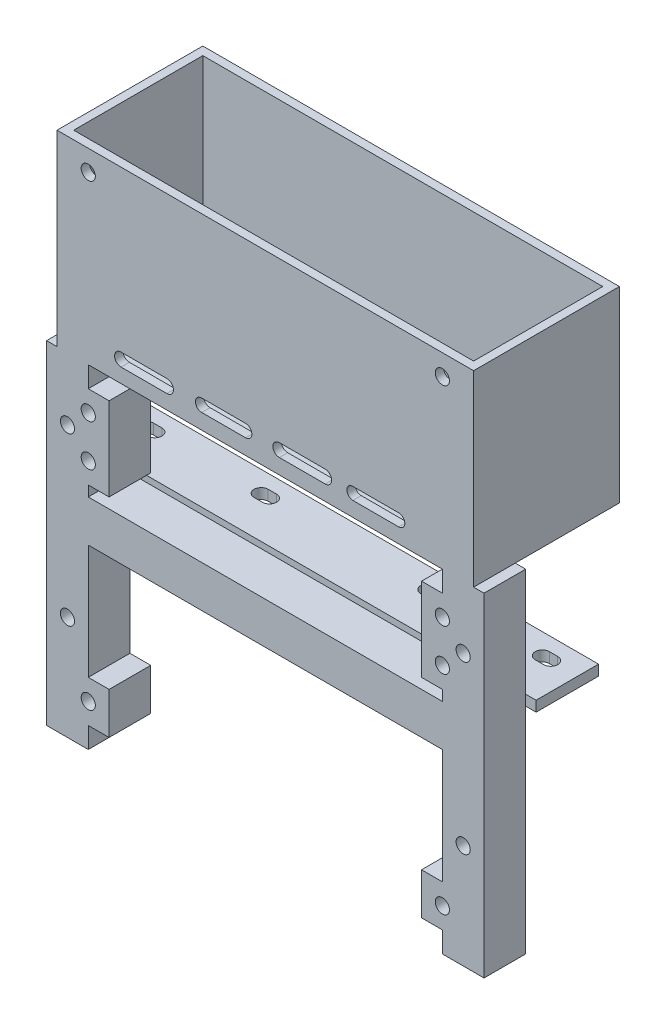
SolidWorks part; units mm, degrees
ref_plane "前视基准面" through (0, 0, 0) normal (0, 0, 1) x (1, 0, 0)
ref_plane "上视基准面" through (0, 0, 0) normal (0, 1, 0) x (1, 0, 0)
ref_plane "右视基准面" through (0, 0, 0) normal (1, 0, 0) x (0, 0, -1)
other "Configuration Table"
sketch "V3 box footprint 100 x 45 mm" plane through (0, 0, 0) normal (0, 0, 1) x (1, 0, 0)
  line L1 (-50, 0) -> (50, 0)
  line L2 (-50, 0) -> (-50, 45)
  line L3 (-50, 45) -> (50, 45)
  line L4 (50, 0) -> (50, 45)
extrude "V3 box height 35 mm" add sketch "V3 box footprint 100 x 45 mm" along normal blind 35
sketch "V3 rear opening 96 x 31 mm" plane through (0, 45, 0) normal (0, 1, 0) x (1, 0, 0)
  line L1 (-48, -2) -> (48, -2)
  line L2 (-48, -2) -> (-48, -33)
  line L3 (-48, -33) -> (48, -33)
  line L4 (48, -2) -> (48, -33)
extrude "V3 cavity all walls 2 mm" cut sketch "V3 rear opening 96 x 31 mm" against normal blind 43
sketch "V3 square beams 10 x 10 pitch 95 mm" plane through (0, 0, 0) normal (0, -1, 0) x (1, 0, 0)
  line L1 (-52.5, 25) -> (-42.5, 25)
  line L2 (-52.5, 25) -> (-52.5, 35)
  line L3 (-52.5, 35) -> (-42.5, 35)
  line L4 (-42.5, 25) -> (-42.5, 35)
  line L6 (42.5, 25) -> (52.5, 25)
  line L7 (42.5, 25) -> (42.5, 35)
  line L8 (42.5, 35) -> (52.5, 35)
  line L9 (52.5, 25) -> (52.5, 35)
extrude "V3 forward beam length 65 mm" add sketch "V3 square beams 10 x 10 pitch 95 mm" along normal blind 65
sketch "V3 left PCB ear profile" plane through (-42.5, 0, 0) normal (1, 0, 0) x (0, 0, -1)
  line L1 (-25, -25) -> (-35, -25)
  line L2 (-25, -25) -> (-25, -15)
  line L3 (-25, -15) -> (-35, -15)
  line L4 (-35, -25) -> (-35, -15)
extrude "V3 left inward ear 5 mm" add sketch "V3 left PCB ear profile" along normal blind 5
sketch "V3 right PCB ear profile" plane through (42.5, 0, 0) normal (-1, 0, 0) x (0, 0, 1)
  line L1 (25, -25) -> (35, -25)
  line L2 (25, -25) -> (25, -15)
  line L3 (25, -15) -> (35, -15)
  line L4 (35, -25) -> (35, -15)
extrude "V3 right inward ear 5 mm" add sketch "V3 right PCB ear profile" along normal blind 5
sketch "V3 PCB roof pair pitch 85 mm" plane through (0, 0, 35) normal (0, 0, 1) x (1, 0, 0)
  circle A0 centre (-42.5, 40) radius 1.7
  circle A1 centre (42.5, 40) radius 1.7
extrude "V3 M3 roof holes diameter 3.4 mm" cut sketch "V3 PCB roof pair pitch 85 mm" against normal blind 2
sketch "V3 PCB forward pair row spacing 60 mm" plane through (0, 0, 35) normal (0, 0, 1) x (1, 0, 0)
  circle A0 centre (-42.5, -20) radius 1.7
  circle A1 centre (42.5, -20) radius 1.7
extrude "V3 M3 PCB ear holes" cut sketch "V3 PCB forward pair row spacing 60 mm" against normal blind 10
sketch "V3 chassis top holes width 95 depth 40 mm" plane through (0, 0, 35) normal (0, 0, 1) x (1, 0, 0)
  circle A0 centre (-47.5, -55) radius 1.7
  circle A1 centre (-47.5, -15) radius 1.7
  circle A2 centre (47.5, -55) radius 1.7
  circle A3 centre (47.5, -15) radius 1.7
extrude "V3 M3 beam top bottom holes" cut sketch "V3 chassis top holes width 95 depth 40 mm" against normal blind 10
sketch "V3 hanging plate offset 26 thickness 2.5 mm" plane through (0, 0, 25) normal (0, 0, -1) x (-1, 0, 0)
  line L1 (55, -28.5) -> (-55, -28.5)
  line L2 (55, -28.5) -> (55, -26)
  line L3 (55, -26) -> (-55, -26)
  line L4 (-55, -28.5) -> (-55, -26)
extrude "V3 mounting plate downward 15 mm width 110" add sketch "V3 hanging plate offset 26 thickness 2.5 mm" along normal blind 15
sketch "V3 slots 6 mm below beam underside centers 20 and 47.5" plane through (0, -28.5, 0) normal (0, -1, 0) x (1, 0, 0)
  line L0 (-48.5, 19) -> (-46.5, 19) construction
  line L1 (-48.5, 20.7) -> (-46.5, 20.7)
  line L2 (-48.5, 17.3) -> (-46.5, 17.3)
  line L3 (-21, 19) -> (-19, 19) construction
  line L4 (-21, 20.7) -> (-19, 20.7)
  line L5 (-21, 17.3) -> (-19, 17.3)
  line L6 (19, 19) -> (21, 19) construction
  line L7 (19, 20.7) -> (21, 20.7)
  line L8 (19, 17.3) -> (21, 17.3)
  line L9 (46.5, 19) -> (48.5, 19) construction
  line L10 (46.5, 20.7) -> (48.5, 20.7)
  line L11 (46.5, 17.3) -> (48.5, 17.3)
  arc A0 (-48.5, 20.7) -> (-48.5, 17.3) centre (-48.5, 19) ccw
  arc A1 (-46.5, 17.3) -> (-46.5, 20.7) centre (-46.5, 19) ccw
  arc A2 (-21, 20.7) -> (-21, 17.3) centre (-21, 19) ccw
  arc A3 (-19, 17.3) -> (-19, 20.7) centre (-19, 19) ccw
  arc A4 (19, 20.7) -> (19, 17.3) centre (19, 19) ccw
  arc A5 (21, 17.3) -> (21, 20.7) centre (21, 19) ccw
  arc A6 (46.5, 20.7) -> (46.5, 17.3) centre (46.5, 19) ccw
  arc A7 (48.5, 17.3) -> (48.5, 20.7) centre (48.5, 19) ccw
  point P2 (-47.5, 19)
  point P7 (-20, 19)
  point P14 (20, 19)
  point P21 (47.5, 19)
  dimension "D1" = 3.4
  dimension "D2" = 2
  dimension "D3" = 3.4
  dimension "D4" = 2
  dimension "D5" = 3.4
  dimension "D6" = 2
  dimension "D7" = 3.4
  dimension "D8" = 2
extrude "Four horizontal slots 3.4 x 5.4 mm" cut sketch "V3 slots 6 mm below beam underside centers 20 and 47.5" against normal blind 2.5
sketch "草图1" plane through (0, 0, 35) normal (0, 0, 1) x (1, 0, 0)
  line L0 (-34.6201, 5) -> (-23.6201, 5) construction
  line L1 (-34.6201, 6.488) -> (-23.6201, 6.488)
  line L2 (-34.6201, 3.512) -> (-23.6201, 3.512)
  line L3 (21.03, 5) -> (32.03, 5) construction
  line L6 (21.03, 6.488) -> (32.03, 6.488)
  line L7 (21.03, 3.512) -> (32.03, 3.512)
  arc A0 (-34.6201, 6.488) -> (-34.6201, 3.512) centre (-34.6201, 5) ccw
  arc A1 (-23.6201, 3.512) -> (-23.6201, 6.488) centre (-23.6201, 5) ccw
  arc A4 (21.03, 6.488) -> (21.03, 3.512) centre (21.03, 5) ccw
  arc A5 (32.03, 3.512) -> (32.03, 6.488) centre (32.03, 5) ccw
  point P2 (-29.1201, 5)
  point P9 (26.53, 5)
sketch "草图2" plane through (0, 0, 0) normal (0, 0, -1) x (-1, 0, 0)
  line L0 (-32.03, 5) -> (-21.03, 5) construction
  line L1 (-32.03, 6.4595) -> (-21.03, 6.4595)
  line L2 (-32.03, 3.5405) -> (-21.03, 3.5405)
  line L3 (23.6201, 5) -> (34.6201, 5) construction
  line L4 (23.6201, 6.5587) -> (34.6201, 6.5587)
  line L5 (23.6201, 3.4413) -> (34.6201, 3.4413)
  arc A0 (-32.03, 6.4595) -> (-32.03, 3.5405) centre (-32.03, 5) ccw
  arc A1 (-21.03, 3.5405) -> (-21.03, 6.4595) centre (-21.03, 5) ccw
  arc A2 (23.6201, 6.5587) -> (23.6201, 3.4413) centre (23.6201, 5) ccw
  arc A3 (34.6201, 3.4413) -> (34.6201, 6.5587) centre (34.6201, 5) ccw
  point P4 (-26.53, 5)
  point P9 (29.1201, 5)
extrude "切除-拉伸1" cut sketch "草图2" against normal through all
sketch "H crossmember 10 x 10 mm at beam midpoint" plane through (-42.5, 0, 0) normal (1, 0, 0) x (0, 0, -1)
  line L1 (-25, -37.5) -> (-35, -37.5)
  line L2 (-25, -37.5) -> (-25, -27.5)
  line L3 (-25, -27.5) -> (-35, -27.5)
  line L4 (-35, -37.5) -> (-35, -27.5)
extrude "H crossmember 85 mm" add sketch "H crossmember 10 x 10 mm at beam midpoint" along normal blind 85
sketch "Beam cavities 6 mm wide preserving screw collars" plane through (0, 0, 35) normal (0, 0, 1) x (1, 0, 0)
  line L1 (-50.5, -65) -> (-44.5, -65)
  line L2 (-50.5, -65) -> (-50.5, -59)
  line L3 (-50.5, -59) -> (-44.5, -59)
  line L4 (-44.5, -65) -> (-44.5, -59)
  line L6 (-50.5, -51) -> (-44.5, -51)
  line L7 (-50.5, -51) -> (-50.5, -24)
  line L8 (-50.5, -24) -> (-44.5, -24)
  line L9 (-44.5, -51) -> (-44.5, -24)
  line L11 (-50.5, -11) -> (-44.5, -11)
  line L12 (-50.5, -11) -> (-50.5, -2)
  line L13 (-50.5, -2) -> (-44.5, -2)
  line L14 (-44.5, -11) -> (-44.5, -2)
  line L16 (44.5, -65) -> (50.5, -65)
  line L17 (44.5, -65) -> (44.5, -59)
  line L18 (44.5, -59) -> (50.5, -59)
  line L19 (50.5, -65) -> (50.5, -59)
  line L21 (44.5, -51) -> (50.5, -51)
  line L22 (44.5, -51) -> (44.5, -24)
  line L23 (44.5, -24) -> (50.5, -24)
  line L24 (50.5, -51) -> (50.5, -24)
  line L26 (44.5, -11) -> (50.5, -11)
  line L27 (44.5, -11) -> (44.5, -2)
  line L28 (44.5, -2) -> (50.5, -2)
  line L29 (50.5, -11) -> (50.5, -2)
extrude "Longitudinal beam walls 2 mm - inner height 6 mm" cut sketch "Beam cavities 6 mm wide preserving screw collars" against normal blind 6 from offset 2
sketch "H crossmember cavity connects both beam cavities" plane through (0, 0, 35) normal (0, 0, 1) x (1, 0, 0)
  line L1 (-44.5, -35.5) -> (44.5, -35.5)
  line L2 (-44.5, -35.5) -> (-44.5, -29.5)
  line L3 (-44.5, -29.5) -> (44.5, -29.5)
  line L4 (44.5, -35.5) -> (44.5, -29.5)
extrude "H crossmember walls 2 mm" cut sketch "H crossmember cavity connects both beam cavities" against normal blind 6 from offset 2
sketch "草图7" plane through (0, 0, 35) normal (0, 0, 1) x (1, 0, 0)
  line L0 (-15.2765, 5.1864) -> (-4.7235, 5.1864) construction
  line L1 (-15.2765, 6.6864) -> (-4.7235, 6.6864)
  line L2 (-15.2765, 3.6864) -> (-4.7235, 3.6864)
  line L3 (3.3727, 5.1864) -> (14.3727, 5.1864) construction
  line L4 (3.3727, 6.6864) -> (14.3727, 6.6864)
  line L5 (3.3727, 3.6864) -> (14.3727, 3.6864)
  arc A0 (-15.2765, 6.6864) -> (-15.2765, 3.6864) centre (-15.2765, 5.1864) ccw
  arc A1 (-4.7235, 3.6864) -> (-4.7235, 6.6864) centre (-4.7235, 5.1864) ccw
  arc A2 (3.3727, 6.6864) -> (3.3727, 3.6864) centre (3.3727, 5.1864) ccw
  arc A3 (14.3727, 3.6864) -> (14.3727, 6.6864) centre (14.3727, 5.1864) ccw
  point P2 (-10, 5.1864)
  point P7 (8.8727, 5.1864)
sketch "草图8" plane through (0, 0, 0) normal (0, 0, -1) x (-1, 0, 0)
  line L0 (-14.3727, 5.1864) -> (-3.3727, 5.1864) construction
  line L1 (-14.3727, 6.733) -> (-3.3727, 6.733)
  line L2 (-14.3727, 3.6397) -> (-3.3727, 3.6397)
  line L3 (4.7235, 5.1864) -> (15.2765, 5.1864) construction
  line L4 (4.7235, 6.6864) -> (15.2765, 6.6864)
  line L5 (4.7235, 3.6864) -> (15.2765, 3.6864)
  arc A0 (-14.3727, 6.733) -> (-14.3727, 3.6397) centre (-14.3727, 5.1864) ccw
  arc A1 (-3.3727, 3.6397) -> (-3.3727, 6.733) centre (-3.3727, 5.1864) ccw
  arc A2 (4.7235, 6.6864) -> (4.7235, 3.6864) centre (4.7235, 5.1864) ccw
  arc A3 (15.2765, 3.6864) -> (15.2765, 6.6864) centre (15.2765, 5.1864) ccw
  point P4 (-8.8727, 5.1864)
  point P9 (10, 5.1864)
extrude "切除-拉伸4" cut sketch "草图8" against normal through all
sketch "V6 extend 10 x 10 hollow beams with 2 mm walls" plane through (0, -65, 0) normal (0, -1, 0) x (1, 0, 0)
  line L1 (-52.5, 25) -> (-42.5, 25)
  line L2 (-52.5, 25) -> (-52.5, 35)
  line L3 (-52.5, 35) -> (-42.5, 35)
  line L4 (-42.5, 25) -> (-42.5, 35)
  line L6 (-50.5, 27) -> (-44.5, 27)
  line L7 (-50.5, 27) -> (-50.5, 33)
  line L8 (-50.5, 33) -> (-44.5, 33)
  line L9 (-44.5, 27) -> (-44.5, 33)
  line L11 (42.5, 25) -> (52.5, 25)
  line L12 (42.5, 25) -> (42.5, 35)
  line L13 (42.5, 35) -> (52.5, 35)
  line L14 (52.5, 25) -> (52.5, 35)
  line L16 (44.5, 27) -> (50.5, 27)
  line L17 (44.5, 27) -> (44.5, 33)
  line L18 (44.5, 33) -> (50.5, 33)
  line L19 (50.5, 27) -> (50.5, 33)
extrude "V6 hollow beam extensions 15 mm" add sketch "V6 extend 10 x 10 hollow beams with 2 mm walls" along normal blind 15
sketch "V6 four full-depth PCB pads centers x42.5 y-70 and -10" plane through (0, 0, 35) normal (0, 0, 1) x (1, 0, 0)
  line L1 (-52.5, -75) -> (-37.5, -75)
  line L2 (-52.5, -75) -> (-52.5, -65)
  line L3 (-52.5, -65) -> (-37.5, -65)
  line L4 (-37.5, -75) -> (-37.5, -65)
  line L6 (37.5, -75) -> (52.5, -75)
  line L7 (37.5, -75) -> (37.5, -65)
  line L8 (37.5, -65) -> (52.5, -65)
  line L9 (52.5, -75) -> (52.5, -65)
  line L11 (-52.5, -15) -> (-37.5, -15)
  line L12 (-52.5, -15) -> (-52.5, -5)
  line L13 (-52.5, -5) -> (-37.5, -5)
  line L14 (-37.5, -15) -> (-37.5, -5)
  line L16 (37.5, -15) -> (52.5, -15)
  line L17 (37.5, -15) -> (37.5, -5)
  line L18 (37.5, -5) -> (52.5, -5)
  line L19 (52.5, -15) -> (52.5, -5)
extrude "V6 solid screw pads with 5 mm inward ears" add sketch "V6 four full-depth PCB pads centers x42.5 y-70 and -10" against normal blind 10
sketch "V6 PCB holes 85 x 60 mm and retained chassis holes" plane through (0, 0, 35) normal (0, 0, 1) x (1, 0, 0)
  circle A0 centre (-42.5, -70) radius 1.7
  circle A1 centre (-42.5, -10) radius 1.7
  circle A2 centre (42.5, -70) radius 1.7
  circle A3 centre (42.5, -10) radius 1.7
  circle A4 centre (-47.5, -15) radius 1.7
  circle A5 centre (47.5, -15) radius 1.7
extrude "V6 four PCB M3 holes through reinforced beam pads" cut sketch "V6 PCB holes 85 x 60 mm and retained chassis holes" against normal blind 10
sketch "V7 retain rail envelopes 10 x 10 length 80 mm" plane through (0, 0, 35) normal (0, 0, 1) x (1, 0, 0)
  line L1 (-52.5, -80) -> (-42.5, -80)
  line L2 (-52.5, -80) -> (-52.5, 0)
  line L3 (-52.5, 0) -> (-42.5, 0)
  line L4 (-42.5, -80) -> (-42.5, 0)
  line L6 (42.5, -80) -> (52.5, -80)
  line L7 (42.5, -80) -> (42.5, 0)
  line L8 (42.5, 0) -> (52.5, 0)
  line L9 (52.5, -80) -> (52.5, 0)
extrude "V7 solid longitudinal beams" add sketch "V7 retain rail envelopes 10 x 10 length 80 mm" against normal blind 10
sketch "V7 retain H crossmember envelope" plane through (0, 0, 35) normal (0, 0, 1) x (1, 0, 0)
  line L1 (-42.5, -37.5) -> (42.5, -37.5)
  line L2 (-42.5, -37.5) -> (-42.5, -27.5)
  line L3 (-42.5, -27.5) -> (42.5, -27.5)
  line L4 (42.5, -37.5) -> (42.5, -27.5)
extrude "V7 solid H crossmember" add sketch "V7 retain H crossmember envelope" against normal blind 10
sketch "V7 preserve all ten existing beam M3 bores" plane through (0, 0, 35) normal (0, 0, 1) x (1, 0, 0)
  circle A0 centre (-47.5, -55) radius 1.7
  circle A1 centre (-47.5, -15) radius 1.7
  circle A2 centre (47.5, -55) radius 1.7
  circle A3 centre (47.5, -15) radius 1.7
  circle A4 centre (-42.5, -70) radius 1.7
  circle A5 centre (-42.5, -20) radius 1.7
  circle A6 centre (-42.5, -10) radius 1.7
  circle A7 centre (42.5, -70) radius 1.7
  circle A8 centre (42.5, -20) radius 1.7
  circle A9 centre (42.5, -10) radius 1.7
extrude "V7 restore chassis and PCB clearance bores" cut sketch "V7 preserve all ten existing beam M3 bores" against normal blind 10
sketch "V7 refill old mounting slots within unchanged plate" plane through (0, -28.5, 0) normal (0, -1, 0) x (1, 0, 0)
  line L1 (-55, 10) -> (55, 10)
  line L2 (-55, 10) -> (-55, 25)
  line L3 (-55, 25) -> (55, 25)
  line L4 (55, 10) -> (55, 25)
extrude "V7 close previous slot positions" add sketch "V7 refill old mounting slots within unchanged plate" against normal blind 2.5
sketch "V7 slot centers z15 - 10 mm below beam underside z25" plane through (0, -28.5, 0) normal (0, -1, 0) x (1, 0, 0)
  line L0 (-48.5, 15) -> (-46.5, 15) construction
  line L1 (-48.5, 16.7) -> (-46.5, 16.7)
  line L2 (-48.5, 13.3) -> (-46.5, 13.3)
  line L3 (-21, 15) -> (-19, 15) construction
  line L4 (-21, 16.7) -> (-19, 16.7)
  line L5 (-21, 13.3) -> (-19, 13.3)
  line L6 (19, 15) -> (21, 15) construction
  line L7 (19, 16.7) -> (21, 16.7)
  line L8 (19, 13.3) -> (21, 13.3)
  line L9 (46.5, 15) -> (48.5, 15) construction
  line L10 (46.5, 16.7) -> (48.5, 16.7)
  line L11 (46.5, 13.3) -> (48.5, 13.3)
  arc A0 (-48.5, 16.7) -> (-48.5, 13.3) centre (-48.5, 15) ccw
  arc A1 (-46.5, 13.3) -> (-46.5, 16.7) centre (-46.5, 15) ccw
  arc A2 (-21, 16.7) -> (-21, 13.3) centre (-21, 15) ccw
  arc A3 (-19, 13.3) -> (-19, 16.7) centre (-19, 15) ccw
  arc A4 (19, 16.7) -> (19, 13.3) centre (19, 15) ccw
  arc A5 (21, 13.3) -> (21, 16.7) centre (21, 15) ccw
  arc A6 (46.5, 16.7) -> (46.5, 13.3) centre (46.5, 15) ccw
  arc A7 (48.5, 13.3) -> (48.5, 16.7) centre (48.5, 15) ccw
  point P2 (-47.5, 15)
  point P7 (-20, 15)
  point P14 (20, 15)
  point P21 (47.5, 15)
  point P28 (0, 0)
  dimension "D1" = 3.4
  dimension "D2" = 2
  dimension "D3" = 3.4
  dimension "D4" = 2
  dimension "D5" = 3.4
  dimension "D6" = 2
  dimension "D7" = 3.4
  dimension "D8" = 2
extrude "V7 four horizontal slots 3.4 x 5.4 mm at 10 mm" cut sketch "V7 slot centers z15 - 10 mm below beam underside z25" against normal blind 2.5
